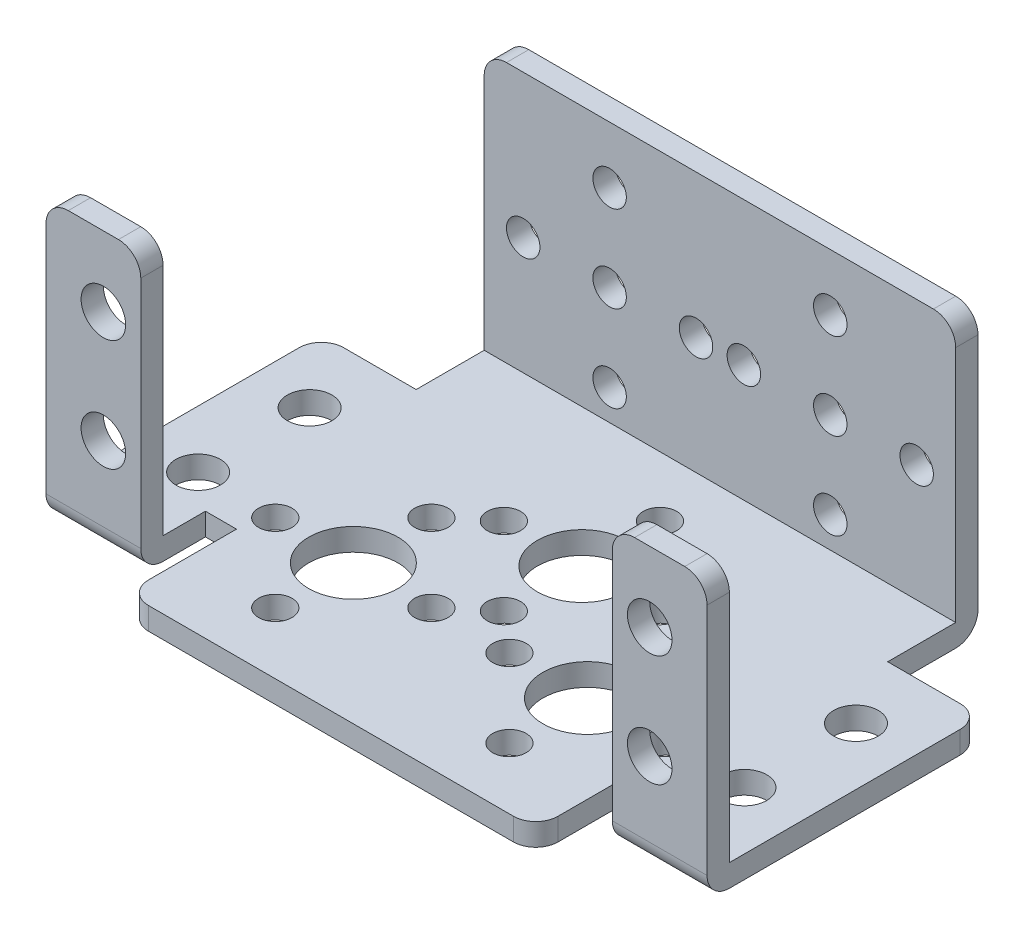
SolidWorks part; units mm, degrees
material "6061 合金"
ref_plane "前视基准面" through (0, 0, 0) normal (0, 0, 1) x (1, 0, 0)
ref_plane "上视基准面" through (0, 0, 0) normal (0, 1, 0) x (1, 0, 0)
ref_plane "右视基准面" through (0, 0, 0) normal (1, 0, 0) x (0, 0, -1)
sketch "草图1" plane through (0, 0, 0) normal (0, 1, 0) x (1, 0, 0)
  line L0 (21.145, 0) -> (-21.145, 0)
  line L1 (-21.145, 0) -> (-21.145, -27)
  line L2 (-21.145, -27) -> (-18.36, -27)
  line L3 (-18.36, -27) -> (-18.36, -36.88)
  line L4 (-18.36, -36.88) -> (18.36, -36.88)
  line L5 (0, 21.0462) -> (0, -51.8744) construction
  line L6 (18.36, -27) -> (18.36, -36.88)
  line L7 (21.145, -27) -> (18.36, -27)
  line L8 (21.145, 0) -> (21.145, -27)
  point P10 (0, -36.88)
  point P13 (0, 0)
  dimension "D1" = 42.29
  dimension "D2" = 36.72
  dimension "D3" = 36.88
  dimension "D4" = 27
extrude "凸台-拉伸1" add sketch "草图1" along normal blind 2
sketch "草图2" plane through (0, 0, 0) normal (1, 0, 0) x (0, 0, -1)
  line L0 (-27, 0) -> (0, 0) construction
  line L1 (0, 2) -> (-2, 2)
  line L2 (0, 2) -> (0, 25.35)
  line L3 (0, 25.35) -> (-2, 25.35)
  line L4 (-2, 2) -> (-2, 25.35)
  dimension "D1" = 25.35
  dimension "D2" = 2
extrude "凸台-拉伸2" add sketch "草图2" along normal up to surface and the other way up to surface up to face at (21.145, 1, 13.5) other way up to face at (-21.145, 1, 13.5)
sketch "草图3" plane through (-21.145, 0, 0) normal (-1, 0, 0) x (0, 0, 1)
  line L0 (32.8, 25) -> (32.8, 0)
  line L2 (27, 0) -> (36.88, 0) construction
  line L3 (32.8, 0) -> (8.1, 0)
  line L4 (0, 0) -> (27, 0) construction
  line L5 (8.1, 0) -> (8.1, 2)
  line L6 (2, 2) -> (27, 2) construction
  line L7 (8.1, 2) -> (30.8, 2)
  line L8 (27, 2) -> (36.88, 2) construction
  line L9 (30.8, 2) -> (30.8, 25)
  line L10 (30.8, 25) -> (32.8, 25)
  line L12 (0, 25.35) -> (0, 0) construction
  dimension "D1" = 2
  dimension "D2" = 24.7
  dimension "D3" = 32.8
  dimension "D4" = 25
extrude "凸台-拉伸3" add sketch "草图3" along normal blind 8.5
mirror "镜向1" about plane through (0, 0, 0) normal (1, 0, 0) of "凸台-拉伸3"
sketch "草图4" plane through (0, 0, 0) normal (0, -1, 0) x (1, 0, 0)
  line L0 (-18.36, 36.88) -> (18.36, 36.88) construction
  line L1 (0, 0) -> (0, 38.6726) construction
  line L2 (29.645, 8.1) -> (21.145, 8.1) construction
  circle A0 centre (10.5, 24.38) radius 7 construction
  circle A1 centre (10.5, 31.38) radius 1.5
  circle A2 centre (17.5, 24.38) radius 1.5
  circle A3 centre (10.5, 17.38) radius 1.5
  circle A4 centre (3.5, 24.38) radius 1.5
  circle A5 centre (-17.5, 24.38) radius 1.5
  circle A6 centre (-10.5, 17.38) radius 1.5
  circle A7 centre (-3.5, 24.38) radius 1.5
  circle A8 centre (-10.5, 31.38) radius 1.5
  circle A9 centre (0, 14.38) radius 7 construction
  circle A10 centre (0, 21.38) radius 1.5
  circle A11 centre (7, 14.38) radius 1.5
  circle A12 centre (0, 7.38) radius 1.5
  circle A13 centre (-7, 14.38) radius 1.5
  circle A14 centre (10.5, 24.38) radius 4
  circle A15 centre (-10.5, 24.38) radius 4
  circle A16 centre (0, 14.38) radius 4
  circle A17 centre (24.5, 24.3) radius 2
  circle A18 centre (24.5, 14.3) radius 2
  circle A19 centre (-24.5, 14.3) radius 2
  circle A20 centre (-24.5, 24.3) radius 2
  point P13 (10.5, 24.38)
  point P37 (0, 14.38)
  dimension "D1" = 14
  dimension "D2" = 3
  dimension "D5" = 14
  dimension "D6" = 3
  dimension "D10" = 8
  dimension "D11" = 8
  dimension "D12" = 4
  dimension "D13" = 4
  dimension "D4" = 5.5
  dimension "D8" = 15.5
  dimension "D9" = 7
  dimension "D14" = 10
  dimension "D15" = 6.2
  dimension "D16" = 49
  dimension "D3" = 4
  dimension "D7" = 4
extrude "切除-拉伸1" cut sketch "草图4" against normal up to next
fillet "圆角1" radius 2 13 edges at (25.395, 0, 32.8) (-25.395, 0, 32.8) (-18.36, 1, 36.88) (18.36, 1, 36.88) (-29.645, 25, 31.8) (29.645, 25, 31.8) (21.145, 25.35, 1) (-21.145, 25.35, 1) (-29.645, 1, 8.1) (29.645, 1, 8.1) (0, 0, 0) (-21.145, 25, 31.8) (21.145, 25, 31.8)
sketch "草图5" plane through (0, 0, 32.8) normal (0, 0, 1) x (1, 0, 0)
  line L1 (-27.645, 25) -> (-23.145, 25) construction
  line L3 (0, 0) -> (0, 35.5925) construction
  circle A0 centre (-24.5, 18.7) radius 2
  circle A1 centre (-24.5, 8.7) radius 2
  circle A2 centre (24.5, 8.7) radius 2
  circle A3 centre (24.5, 18.7) radius 2
  dimension "D1" = 4
  dimension "D2" = 4
  dimension "D3" = 10
  dimension "D4" = 6.3
  dimension "D5" = 49
extrude "切除-拉伸2" cut sketch "草图5" against normal up to next
sketch "草图6" plane through (0, 0, 2) normal (0, 0, 1) x (1, 0, 0)
  line L0 (19.145, 25.35) -> (-19.145, 25.35) construction
  line L1 (0, 2) -> (0, 25.35) construction
  line L2 (21.145, 2) -> (-21.145, 2) construction
  line L4 (-21.145, 2) -> (-21.145, 23) construction
  circle A0 centre (-9.895, 12.5) radius 1.5
  circle A1 centre (-9.895, 12.5) radius 7.75 construction
  circle A2 centre (-17.645, 12.5) radius 1.5
  circle A3 centre (-9.895, 20.25) radius 1.5
  circle A4 centre (-2.145, 12.5) radius 1.5
  circle A5 centre (-9.895, 4.75) radius 1.5
  circle A6 centre (9.895, 4.75) radius 1.5
  circle A7 centre (9.895, 12.5) radius 1.5
  circle A8 centre (2.145, 12.5) radius 1.5
  circle A9 centre (9.895, 20.25) radius 1.5
  circle A10 centre (17.645, 12.5) radius 1.5
  point P14 (-9.895, 12.5)
  dimension "D1" = 3
  dimension "D2" = 15.5
  dimension "D3" = 3
  dimension "D5" = 3.6
  dimension "D6" = 2
  dimension "D4" = 4
extrude "切除-拉伸3" cut sketch "草图6" against normal through all
